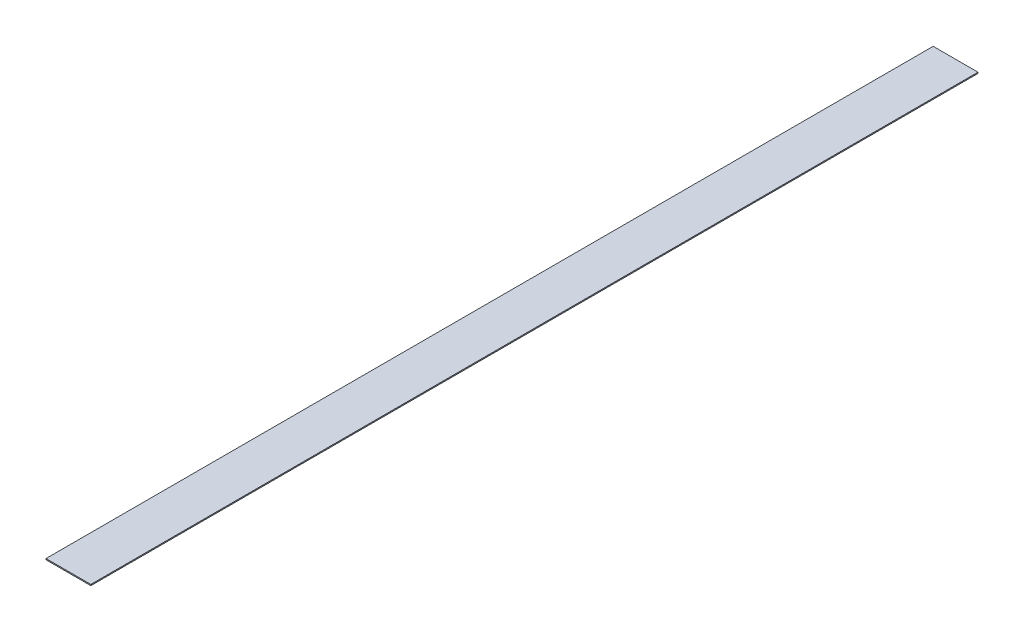
SolidWorks part; units mm, degrees
ref_plane "Front Plane" through (0, 0, 0) normal (0, 0, 1) x (1, 0, 0)
ref_plane "Top Plane" through (0, 0, 0) normal (0, 1, 0) x (1, 0, 0)
ref_plane "Right Plane" through (0, 0, 0) normal (1, 0, 0) x (0, 0, -1)
sketch "Sketch1" plane through (0, 0, 0) normal (0, 1, 0) x (1, 0, 0)
  line L0 (-25.4, 45.466) -> (25.4, 85.6142)
  line L1 (-25.4, -502.666) -> (25.4, -502.666)
  line L2 (-25.4, -502.666) -> (-25.4, 502.666)
  line L3 (-25.4, 502.666) -> (25.4, 502.666)
  line L4 (25.4, -502.666) -> (25.4, 502.666)
  line L5 (-25.4, -502.666) -> (25.4, 502.666) construction
  line L6 (-25.4, 502.666) -> (25.4, -502.666) construction
  point P0 (0, 0)
  dimension "D1" = 50.8
  dimension "D2" = 1005.332
  dimension "D3" = 141.68
  dimension "D4" = 457.2
extrude "Boss-Extrude1" add sketch "Sketch1" along normal blind 1.27 contours L1 L4 L0 L2
